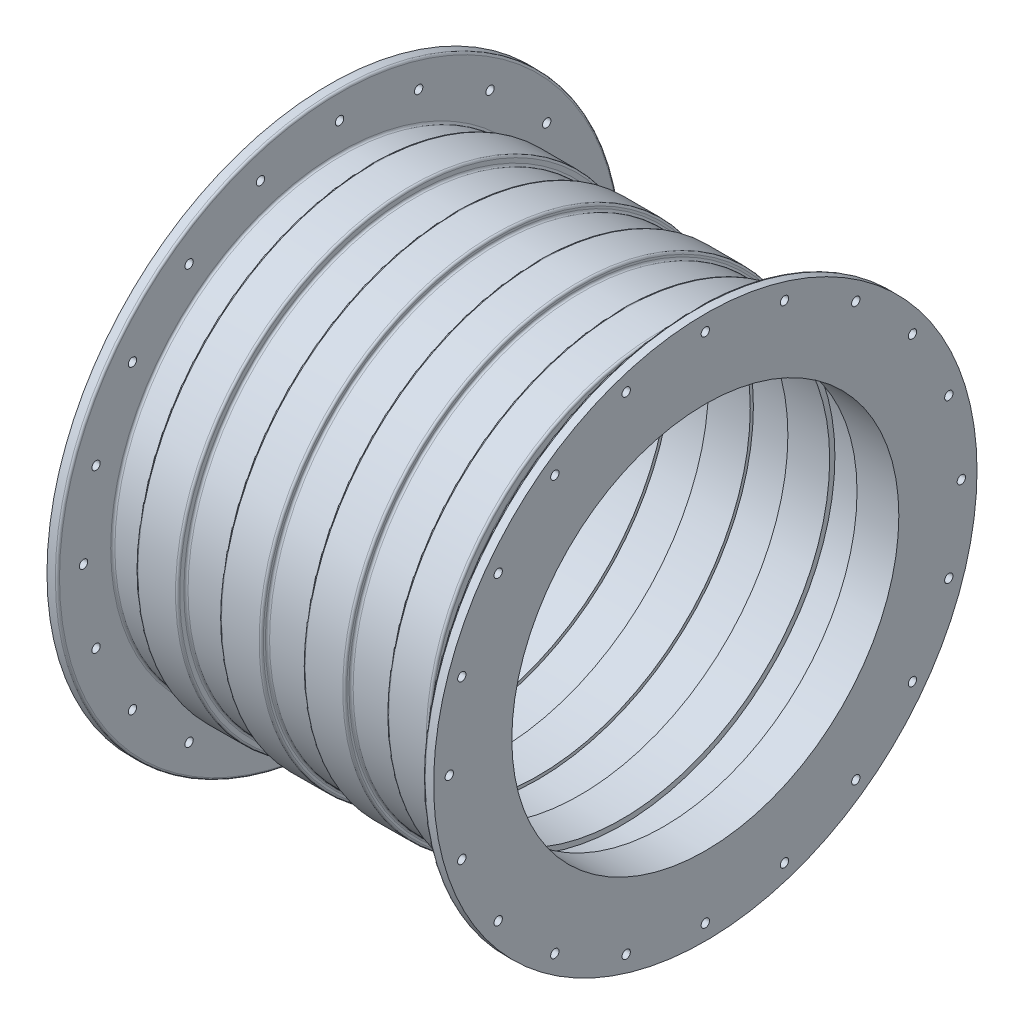
SolidWorks part; units mm, degrees
ref_plane "Front Plane" through (0, 0, 0) normal (0, 0, 1) x (1, 0, 0)
ref_plane "Top Plane" through (0, 0, 0) normal (0, 1, 0) x (1, 0, 0)
ref_plane "Right Plane" through (0, 0, 0) normal (1, 0, 0) x (0, 0, -1)
sketch "Sketch1" plane through (0, 0, 0) normal (0, 0, 1) x (1, 0, 0)
  line L0 (120.3998, 0) -> (-120.3998, 0) construction
  line L1 (-56.7143, 101.5) -> (-56.7143, 105.5)
  line L2 (-76.7143, 101.5) -> (-56.7143, 101.5)
  line L3 (-76.7143, 101.5) -> (-76.7143, 135)
  line L4 (-76.7143, 135) -> (-71.7143, 135)
  line L5 (-71.7143, 135) -> (-71.7143, 108.5)
  line L6 (-71.7143, 108.5) -> (-56.7143, 108.5)
  line L7 (-56.7143, 108.5) -> (-56.7143, 112.5)
  line L8 (-56.7143, 112.5) -> (-36.7143, 112.5)
  line L9 (-36.7143, 112.5) -> (-36.7143, 108.5)
  line L10 (-36.7143, 102.502) -> (-16.7143, 102.502)
  line L11 (-36.7143, 105.5) -> (-36.7143, 102.502)
  line L12 (-36.7143, 108.5) -> (-16.7143, 108.5)
  line L13 (-16.7143, 108.5) -> (-16.7143, 112.5)
  line L14 (-16.7143, 102.502) -> (-16.7143, 104)
  line L15 (-16.7143, 112.5) -> (3.2857, 112.5)
  line L16 (-56.7143, 105.5) -> (-36.7143, 105.5)
  line L17 (3.2857, 112.5) -> (3.2857, 109.5)
  line L18 (3.2857, 109.5) -> (23.2857, 109.5)
  line L19 (23.2857, 109.5) -> (23.2857, 112.5)
  line L20 (23.2857, 112.5) -> (43.2857, 112.5)
  line L21 (23.2857, 101.5) -> (23.2857, 103)
  line L22 (23.2857, 103) -> (43.2857, 103)
  line L23 (43.2857, 112.5) -> (43.2857, 109.5)
  line L24 (43.2857, 109.5) -> (63.2857, 109.5)
  line L25 (-16.7143, 104) -> (3.2857, 104)
  line L26 (3.2857, 104) -> (3.2857, 101.5)
  line L27 (3.2857, 101.5) -> (23.2857, 101.5)
  line L28 (63.2857, 109.5) -> (63.2857, 112.5)
  line L29 (43.2857, 99.5) -> (63.2857, 99.5)
  line L30 (63.2857, 99.5) -> (63.2857, 102)
  line L31 (43.2857, 99.5) -> (43.2857, 103)
  line L32 (63.2857, 102) -> (83.2857, 102)
  line L33 (63.2857, 112.5) -> (83.2857, 112.5)
  line L34 (83.2857, 112.5) -> (83.2857, 107.5872)
  line L35 (83.2857, 107.5872) -> (98.2857, 107.5872)
  line L36 (98.2857, 107.5872) -> (98.2857, 130)
  line L37 (98.2857, 130) -> (103.2857, 130)
  line L43 (103.2857, 92.5872) -> (83.2857, 92.5872)
  line L44 (83.2857, 92.5872) -> (83.2857, 102)
  line L45 (103.2857, 130) -> (103.2857, 92.5872)
  point P3 (0, 0)
  point P4 (0, 0)
  point P17 (-46.7143, 105.5)
  dimension "D1" = 5
  dimension "D2" = 20
  dimension "D3" = 5.998
  dimension "D4" = 4
  dimension "D5" = 101.5
  dimension "D6" = 135
  dimension "D7" = 105.5
  dimension "D8" = 7
  dimension "D9" = 15
  dimension "D10" = 4
  dimension "D11" = 104
  dimension "D12" = 8
  dimension "D13" = 103
  dimension "D14" = 10
  dimension "D15" = 102
  dimension "D16" = 130
  dimension "D17" = 15
  dimension "D18" = 15
revolve "Revolve1" add sketch "Sketch1" angle 360 about L0
sketch "Sketch2" plane through (-76.7143, 0, 0) normal (-1, 0, 0) x (0, 0, 1)
  circle A0 centre (0, 122.5) radius 2
  dimension "D1" = 4
  dimension "D2" = 122.5
extrude "Cut-Extrude1" cut sketch "Sketch2" against normal through all
pattern_circular "CirPattern1" count 20 over 360 about axis through (0, 0, 0) along (1, 0, 0) of "Cut-Extrude1"
fillet "Fillet1" radius 1 19 edges at (-71.7143, 0, -108.5) (98.2857, 0, -107.5872) (83.2857, 0, -107.5872) (83.2857, 0, -112.5) (63.2857, 0, -112.5) (63.2857, 0, -109.5) (43.2857, 0, -109.5) (43.2857, 0, -112.5) (23.2857, 0, -112.5) (23.2857, 0, -109.5) (3.2857, 0, -109.5) (3.2857, 0, -112.5) (-16.7143, 0, -112.5) (-16.7143, 0, -108.5) (-36.7143, 0, -108.5) (-36.7143, 0, -112.5) (-56.7143, 0, -112.5) (98.2857, 0, -130) (-71.7143, 0, -135)
